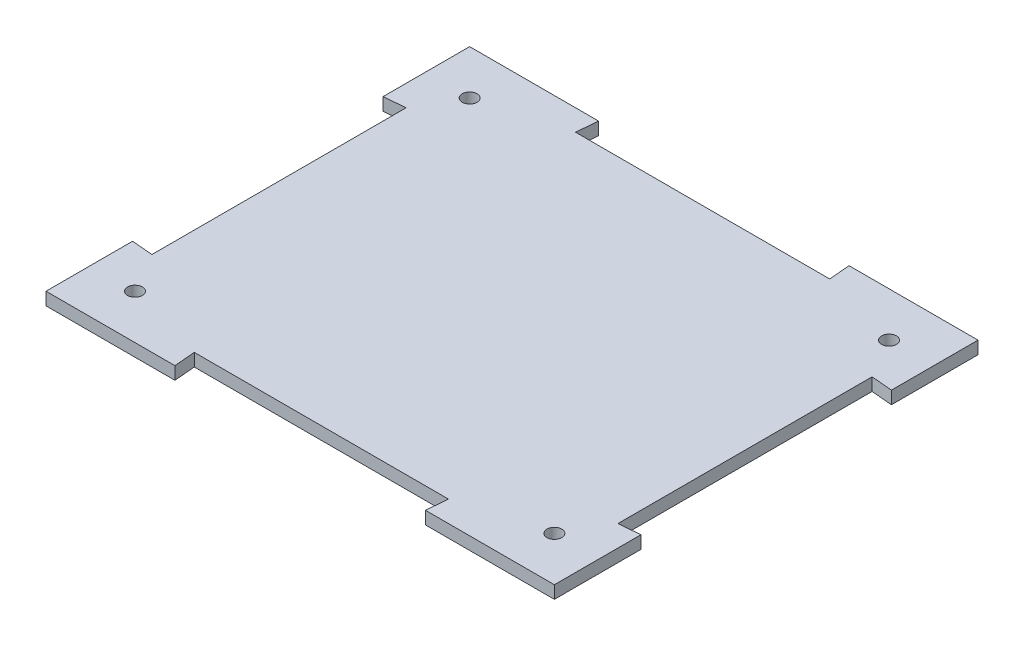
SolidWorks part; units mm, degrees
ref_plane "Front Plane" through (0, 0, 0) normal (0, 0, 1) x (1, 0, 0)
ref_plane "Top Plane" through (0, 0, 0) normal (0, 1, 0) x (1, 0, 0)
ref_plane "Right Plane" through (0, 0, 0) normal (1, 0, 0) x (0, 0, -1)
sketch "Sketch1" plane through (0, 0, 0) normal (0, 1, 0) x (1, 0, 0)
  line L1 (0, 0) -> (120, 0)
  line L2 (0, 0) -> (0, 100)
  line L3 (0, 100) -> (120, 100)
  line L4 (120, 0) -> (120, 100)
  dimension "D1" = 100
  dimension "D2" = 120
extrude "plateform" add sketch "Sketch1" along normal blind 3
sketch "Sketch2" plane through (0, 3, 0) normal (0, 1, 0) x (1, 0, 0)
  line L0 (0, 79.5626) -> (5, 80)
  line L1 (0, 100) -> (0, 0) construction
  line L2 (5, 80) -> (5, 20)
  line L3 (5, 20) -> (0, 20.4374)
  line L4 (0, 20.4374) -> (0, 79.5626)
  line L5 (30.4374, 100) -> (30, 95)
  line L6 (120, 100) -> (0, 100) construction
  line L7 (30, 95) -> (90, 95)
  line L8 (90, 95) -> (89.5626, 100)
  line L9 (89.5626, 100) -> (30.4374, 100)
  line L10 (120, 79.5626) -> (115, 80)
  line L11 (120, 0) -> (120, 100) construction
  line L12 (115, 80) -> (115, 20)
  line L13 (115, 20) -> (120, 20.4374)
  line L14 (120, 20.4374) -> (120, 79.5626)
  line L16 (30.4374, 0) -> (30, 5)
  line L17 (0, 0) -> (120, 0) construction
  line L18 (30, 5) -> (90, 5)
  line L19 (90, 5) -> (89.5626, 0)
  line L20 (89.5626, 0) -> (30.4374, 0)
  point P27 (0, 50)
  point P28 (60, 100)
  point P29 (120, 50)
  point P30 (60, 0)
  dimension "D1" = 60
  dimension "D2" = 85
  dimension "D3" = 5
extrude "cut_arms" cut sketch "Sketch2" against normal blind 10
sketch "Sketch6" plane through (0, 3, 0) normal (0, 1, 0) x (1, 0, 0)
  line L0 (5, 20) -> (5, 80) construction
  line L1 (10.5, 89.5) -> (109.5, 89.5) construction
  line L2 (10.5, 89.5) -> (10.5, 10.5) construction
  line L3 (10.5, 10.5) -> (109.5, 10.5) construction
  line L4 (109.5, 89.5) -> (109.5, 10.5) construction
  line L5 (30, 95) -> (90, 95) construction
  line L6 (115, 80) -> (115, 20) construction
  line L7 (90, 5) -> (30, 5) construction
  circle A0 centre (10.5, 89.5) radius 1.75
  circle A1 centre (109.5, 89.5) radius 1.75
  circle A2 centre (109.5, 10.5) radius 1.75
  circle A3 centre (10.5, 10.5) radius 1.75
  dimension "D1" = 3.5
  dimension "D2" = 5.5
  dimension "D3" = 5.5
  dimension "D4" = 5.5
  dimension "D5" = 5.5
extrude "holes_spacers" cut sketch "Sketch6" against normal up to next
equation "\"D4@Sketch6\"=\"D2@Sketch6\""
equation "\"D5@Sketch6\"=\"D3@Sketch6\""
